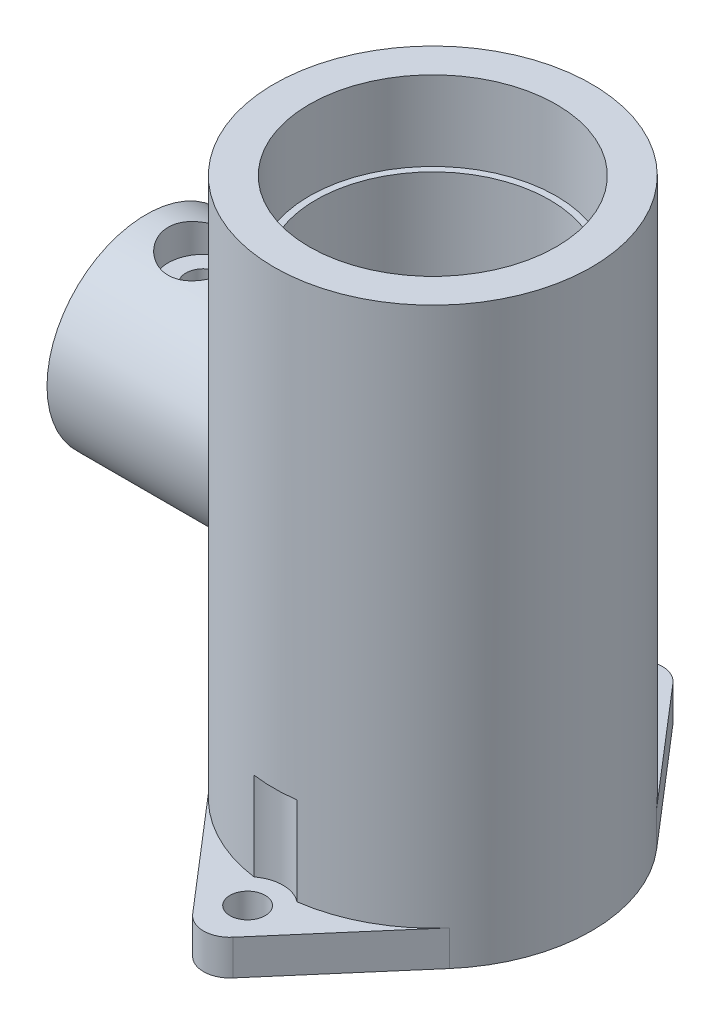
SolidWorks part; units mm, degrees
ref_plane "Plan de face" through (0, 0, 0) normal (0, 0, 1) x (1, 0, 0)
ref_plane "Plan de dessus" through (0, 0, 0) normal (0, 1, 0) x (1, 0, 0)
ref_plane "Plan de droite" through (0, 0, 0) normal (1, 0, 0) x (0, 0, -1)
sketch "Esquisse1" plane through (0, 0, 0) normal (0, 1, 0) x (1, 0, 0)
  circle A0 centre (0, 0) radius 18
  dimension "D1" = 36
extrude "Boss.-Extru.1" add sketch "Esquisse1" along normal blind 65.18
ref_plane "Plan1" through (-16.5, 0, 0) normal (1, 0, 0) x (0, 0, -1)
sketch "Esquisse2" plane through (-16.5, 0, 0) normal (1, 0, 0) x (0, 0, -1)
  line L0 (0, 18.15) -> (0, -18.15) construction
  line L1 (18.15, 0) -> (-18.15, 0) construction
  circle A0 centre (0, 33.87) radius 11.25
  dimension "D2" = 22.5
  dimension "D1" = 33.87
extrude "Boss.-Extru.3" add sketch "Esquisse2" along normal blind 6 and the other way blind 16 contours A0
sketch "Esquisse3" plane through (-32.5, 0, 0) normal (-1, 0, 0) x (0, 0, 1)
  circle A0 centre (0, 33.87) radius 4.8
  circle A1 centre (0, 33.87) radius 11.25 construction
  dimension "D1" = 9.6
extrude "Enlèv. mat.-Extru.1" cut sketch "Esquisse3" against normal blind 13
sketch "Esquisse4" plane through (0, 65.18, 0) normal (0, 1, 0) x (1, 0, 0)
  circle A0 centre (0, 0) radius 14
  circle A1 centre (0, 0) radius 18 construction
  dimension "D1" = 28
extrude "Enlèv. mat.-Extru.2" cut sketch "Esquisse4" against normal blind 9
sketch "Esquisse5" plane through (0, 56.18, 0) normal (0, 1, 0) x (1, 0, 0)
  circle A0 centre (0, 0) radius 10
  dimension "D1" = 20
extrude "Enlèv. mat.-Extru.3" cut sketch "Esquisse5" against normal through all
sketch "Esquisse8" plane through (0, 0, 0) normal (0, 1, 0) x (1, 0, 0)
  line L0 (13.6452, 11.7391) -> (2.2742, 24.9565)
  line L1 (-2.2742, 24.9565) -> (-13.6452, 11.7391)
  line L2 (0, -19.8) -> (0, 19.8) construction
  circle A0 centre (0, 0) radius 18 construction
  arc A1 (2.2742, 24.9565) -> (-2.2742, 24.9565) centre (0, 23) ccw
  arc A2 (-13.6452, 11.7391) -> (13.6452, 11.7391) centre (0, 0) cw
  circle A3 centre (0, 0) radius 18 construction
  dimension "D1" = 3
  dimension "D3" = 0
  dimension "D2" = 23
extrude "Boss.-Extru.4" add sketch "Esquisse8" along normal blind 4
sketch "Esquisse9" plane through (0, 4, 0) normal (0, 1, 0) x (1, 0, 0)
  circle A0 centre (0, 21) radius 2
  arc A3 (2.2742, 24.9565) -> (-2.2742, 24.9565) centre (0, 23) ccw construction
  dimension "D1" = 4
  dimension "D2" = 5
extrude "Enlèv. mat.-Extru.4" cut sketch "Esquisse9" against normal through all
mirror "Symétrie3" about plane through (0, 0, 0) normal (1, 0, 0) of "Enlèv. mat.-Extru.4", "Boss.-Extru.4" second plane through (0, 0, 0) second plane normal (0, 0, 1)
ref_plane "Plan3- Symétrie vis barre" through (0, 33.87, 0) normal (0, 1, 0) x (1, 0, 0)
ref_plane "Plan4" through (0, 45.12, 0) normal (0, 1, 0) x (1, 0, 0)
sketch "Esquisse11" plane through (0, 45.12, 0) normal (0, 1, 0) x (1, 0, 0)
  line L0 (-32.5, 11.25) -> (-32.5, -11.25) construction
  line L1 (-27.775, 0) -> (27.775, 0) construction
  circle A0 centre (-26, 0) radius 4
  dimension "D2" = 8
  dimension "D1" = 6.5
extrude "Enlèv. mat.-Extru.5" cut sketch "Esquisse11" against normal blind 3.5
sketch "Esquisse12" plane through (0, 41.62, 0) normal (0, 1, 0) x (1, 0, 0)
  circle A0 centre (-26, 0) radius 2
  circle A2 centre (-26, 0) radius 4 construction
  dimension "D1" = 4
extrude "Enlèv. mat.-Extru.6" cut sketch "Esquisse12" against normal blind 3.5
mirror "Symétrie4" about plane through (0, 0, 0) normal (0, 0, 1) of "Enlèv. mat.-Extru.5", "Enlèv. mat.-Extru.6" second plane through (0, 33.87, 0) second plane normal (0, 1, 0)
sketch "Esquisse13" plane through (0, 0, 0) normal (0, -1, 0) x (1, 0, 0)
  circle A0 centre (0, 0) radius 13.25
  dimension "D1" = 26.5
extrude "Enlèv. mat.-Extru.7" cut sketch "Esquisse13" against normal blind 75
sketch "Esquisse14" plane through (0, 4, 0) normal (0, 1, 0) x (1, 0, 0)
  arc A0 (-2.4438, -17.8333) -> (2.4438, -17.8333) centre (0, -21) cw
  arc A1 (-13.6452, -11.7391) -> (13.6452, -11.7391) centre (0, 0) ccw construction
  arc A2 (-2.4438, -17.8333) -> (2.4438, -17.8333) centre (0, 0) ccw
  circle A4 centre (0, -21) radius 2 construction
  circle A5 centre (0, 0) radius 18 construction
  dimension "D1" = 4
extrude "Enlèv. mat.-Extru.8" cut sketch "Esquisse14" along normal blind 10
ref_plane "Plan5" through (0, 0, 0) normal (0, 0, 1) x (1, 0, 0)
mirror "Symétrie5" about plane through (0, 0, 0) normal (0, 0, 1) of "Enlèv. mat.-Extru.8"
